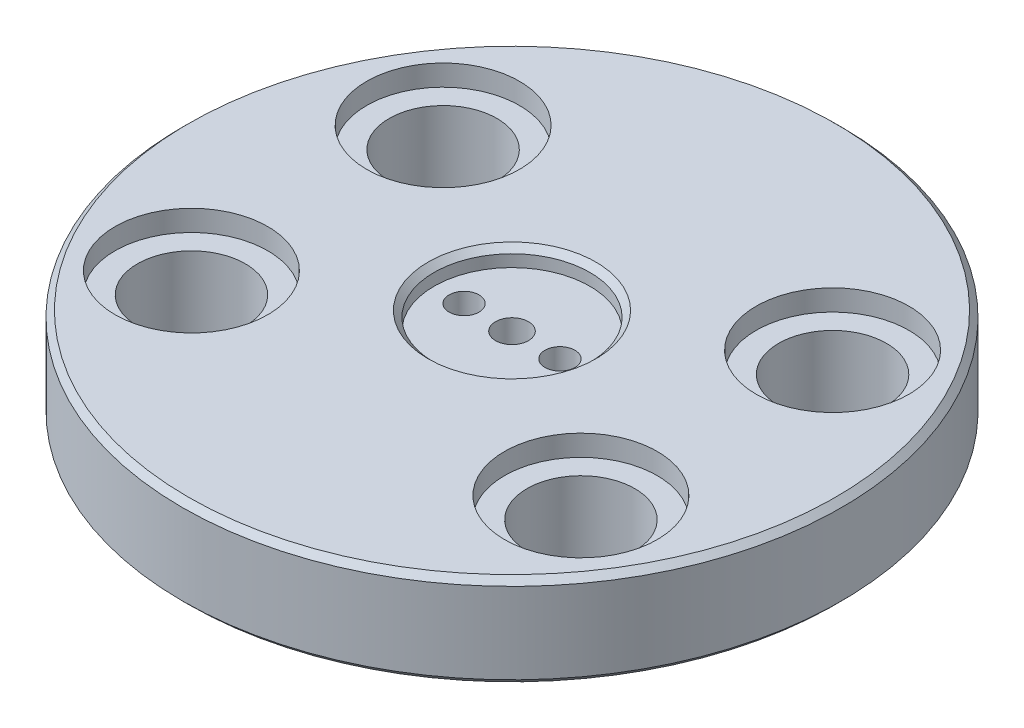
SolidWorks part; units mm, degrees
ref_plane "Front Plane" through (0, 0, 0) normal (0, 0, 1) x (1, 0, 0)
ref_plane "Top Plane" through (0, 0, 0) normal (0, 1, 0) x (1, 0, 0)
ref_plane "Right Plane" through (0, 0, 0) normal (1, 0, 0) x (0, 0, -1)
sketch "Sketch1" plane through (0, 0, 0) normal (0, 1, 0) x (1, 0, 0)
  circle A0 centre (0, 0) radius 55
  dimension "D1" = 110
extrude "Boss-Extrude1" add sketch "Sketch1" along normal blind 15.5
sketch "Sketch2" plane through (0, 15.5, 0) normal (0, 1, 0) x (1, 0, 0)
  line L1 (-32.5, 21) -> (32.5, 21) construction
  line L2 (-32.5, 21) -> (-32.5, -21) construction
  line L3 (-32.5, -21) -> (32.5, -21) construction
  line L4 (32.5, 21) -> (32.5, -21) construction
  line L5 (-32.5, 21) -> (32.5, -21) construction
  line L6 (-32.5, -21) -> (32.5, 21) construction
  point P0 (0, 0)
  dimension "D1" = 42
  dimension "D2" = 65
hole_wizard "CBORE for M6 Hex Socket Head Cap Screw1" positions "Sketch3" profile "Sketch4" counterbore size "M6" standard "ISO" end condition through all
sketch "Sketch3" plane through (0, 15.5, 0) normal (0, 1, 0) x (1, 0, 0)
  point P0 (-32.5, 21)
  point P3 (32.5, 21)
  point P6 (32.5, -21)
  point P9 (-32.5, -21)
sketch "Sketch4" plane through (-32.5, 15.5, -21) normal (1, 0, 0) x (0, 0, 1)
  line L0 (0, 0) -> (0, 15.5)
  line L1 (0, 15.5) -> (9, 15.5)
  line L3 (9, 15.5) -> (9, 3.5)
  line L4 (9, 3.5) -> (12.75, 3.5)
  line L5 (12.75, 3.5) -> (12.75, 0)
  line L7 (12.75, 0) -> (0, 0)
  line L11 (0, -6.35) -> (0, 107.95) construction
  dimension "Thru Hole Dia." = 18
  dimension "Thru Hole Depth" = 15.5
  dimension "C'Bore Dia." = 25.5
  dimension "C'Bore Depth" = 3.5
sketch "Sketch5" plane through (0, 15.5, 0) normal (0, 1, 0) x (1, 0, 0)
  circle A0 centre (0, 0) radius 13
  dimension "D1" = 26
extrude "Cut-Extrude1" cut sketch "Sketch5" against normal blind 3
sketch "Sketch6" plane through (0, 12.5, 0) normal (0, 1, 0) x (1, 0, 0)
  line L0 (-13, 0) -> (13, 0) construction
  circle A0 centre (0, 0) radius 13 construction
  point P8 (0, 0)
hole_wizard "Ø5.0mm Dowel Hole1" positions "Sketch7" profile "Sketch8" hole size "Ø5.0" standard "ISO" end condition through all
sketch "Sketch7" plane through (0, 12.5, 0) normal (0, 1, 0) x (1, 0, 0)
  line L0 (-13, 0) -> (13, 0) construction
  point P0 (-8, 0)
  point P4 (8, 0)
  dimension "D1" = 8
  dimension "D2" = 16
sketch "Sketch8" plane through (-8, 12.5, 0) normal (1, 0, 0) x (0, 0, 1)
  line L0 (0, 0) -> (0, 12.5)
  line L1 (0, 12.5) -> (2.5, 12.5)
  line L2 (2.5, 12.5) -> (2.5, 0)
  line L5 (2.5, 0) -> (0, 0)
  line L11 (0, -6.35) -> (0, 107.95) construction
  dimension "Thru Hole Dia." = 5
  dimension "Thru Hole Depth" = 12.5
chamfer "Chamfer1" distance 1 angle 45 2 edges at (0, 15.5, 13) (0, 15.5, 55)
chamfer "Chamfer2" distance 1 angle 45 1 edges at (0, 0, 55)
hole_wizard "CBORE for M5 Hex Socket Head Cap Screw1" positions "Sketch9" profile "Sketch10" counterbore size "M5" standard "ISO" end condition through all
sketch "Sketch9" plane through (0, 0, 0) normal (0, -1, 0) x (-1, 0, 0)
  point P0 (0, 0)
sketch "Sketch10" plane through (0, 0, 0) normal (1, 0, 0) x (0, 0, -1)
  line L0 (0, 0) -> (0, 15.5)
  line L1 (0, 15.5) -> (2.75, 15.5)
  line L3 (2.75, 15.5) -> (2.75, 6)
  line L4 (2.75, 6) -> (4.5, 6)
  line L5 (4.5, 6) -> (4.5, 0)
  line L7 (4.5, 0) -> (0, 0)
  line L11 (0, -6.35) -> (0, 107.95) construction
  dimension "Thru Hole Dia." = 5.5
  dimension "Thru Hole Depth" = 15.5
  dimension "C'Bore Dia." = 9
  dimension "C'Bore Depth" = 6
